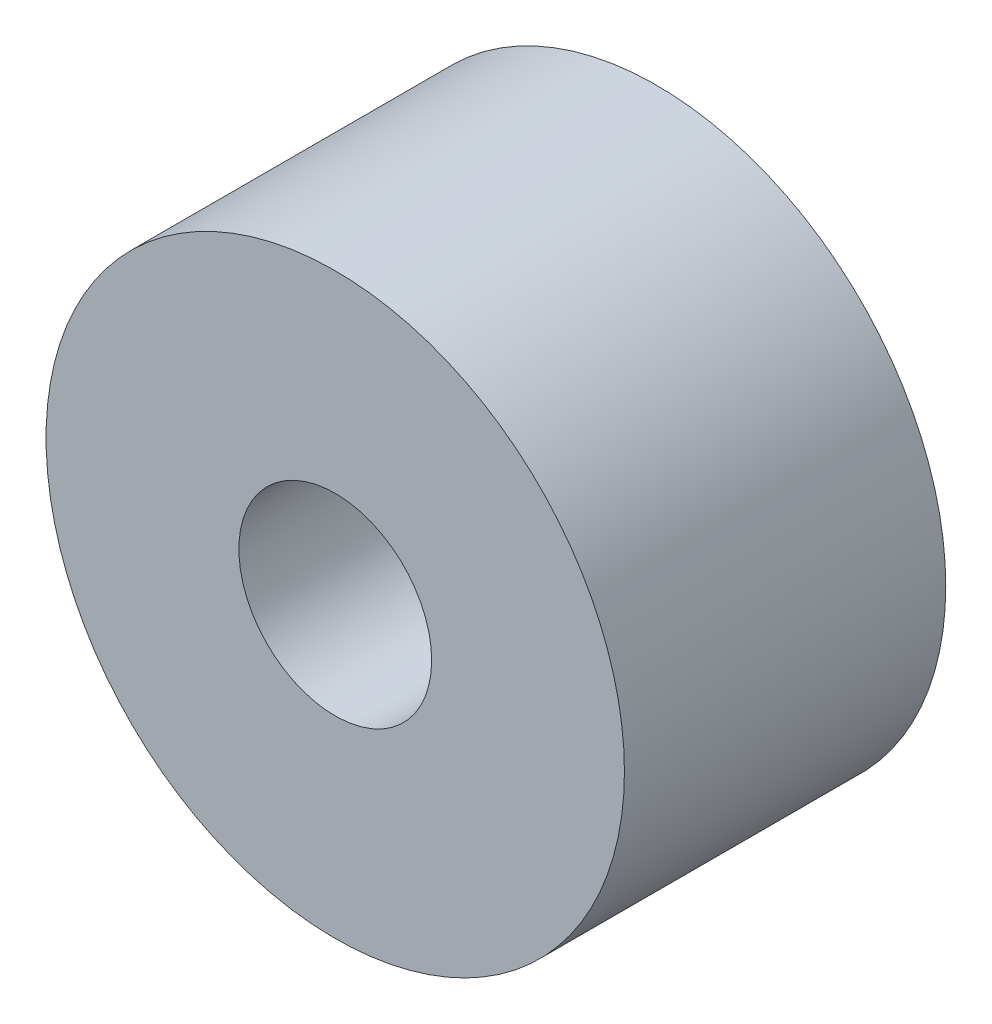
SolidWorks part; units mm, degrees
material "Brass"
ref_plane "Front Plane" through (0, 0, 0) normal (0, 0, 1) x (1, 0, 0)
ref_plane "Top Plane" through (0, 0, 0) normal (0, 1, 0) x (1, 0, 0)
ref_plane "Right Plane" through (0, 0, 0) normal (1, 0, 0) x (0, 0, -1)
sketch "Sketch1" plane through (0, 0, 0) normal (0, 0, 1) x (1, 0, 0)
  circle A0 centre (0, 0) radius 2.25
  circle A1 centre (0, 0) radius 0.75
  dimension "D1" = 4.5
  dimension "D2" = 1.5
extrude "Boss-Extrude1" add sketch "Sketch1" along normal blind 2.5
